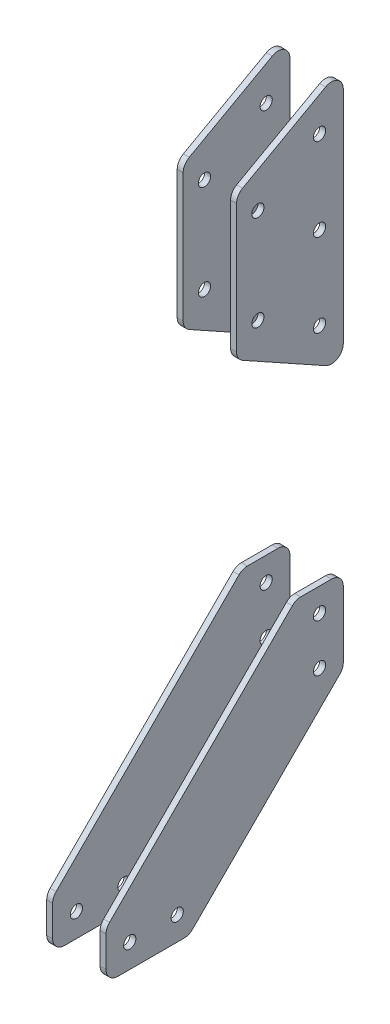
SolidWorks part; units mm, degrees
ref_plane "Front Plane" through (0, 0, 0) normal (0, 0, 1) x (1, 0, 0)
ref_plane "Top Plane" through (0, 0, 0) normal (0, 1, 0) x (1, 0, 0)
ref_plane "Right Plane" through (0, 0, 0) normal (1, 0, 0) x (0, 0, -1)
sketch "Sketch1" plane through (12.7, 0, 0) normal (1, 0, 0) x (0, 0, -1)
  line L0 (-44.45, 317.5) -> (-44.45, 241.3)
  line L1 (-44.45, 241.3) -> (12.7, 209.55)
  line L2 (12.7, 209.55) -> (12.7, 349.25)
  line L3 (12.7, 349.25) -> (-44.45, 317.5)
  line L4 (-44.45, 279.4) -> (12.7, 279.4) construction
  line L5 (0, 279.4) -> (-25.4, 279.4) construction
  line L6 (-44.45, 317.5) -> (-44.45, 241.3) construction
  line L7 (12.7, 406.4) -> (12.7, 12.7) construction
  line L8 (-12.7, 317.5) -> (-44.45, 317.5) construction
  line L9 (-12.7, 114.3) -> (-114.3, 12.7)
  line L10 (-114.3, 12.7) -> (-114.3, -12.7)
  line L11 (-114.3, -12.7) -> (-69.85, -12.7)
  line L12 (-69.85, -12.7) -> (12.7, 69.85)
  line L13 (12.7, 69.85) -> (12.7, 114.3)
  line L14 (12.7, 114.3) -> (-12.7, 114.3)
  line L15 (-355.6, -12.7) -> (152.4, -12.7) construction
  line L16 (-114.3, -12.7) -> (12.7, 114.3) construction
  dimension "D1" = 139.7
  dimension "D2" = 127
  dimension "D3" = 127
  dimension "D4" = 101.6
  dimension "D5" = 82.55
extrude "Boss-Extrude1" add sketch "Sketch1" along normal blind 3.175
sketch "Sketch4" plane through (15.875, 0, 0) normal (1, 0, 0) x (0, 0, -1)
  line L0 (0, 279.4) -> (0, 406.4) construction
  line L1 (0, 279.4) -> (0, 12.7) construction
  line L2 (-355.6, 0) -> (152.4, 0) construction
  line L3 (0, 323.85) -> (0, 234.95) construction
  line L5 (0, 101.6) -> (0, 76.2) construction
  line L7 (-101.6, 0) -> (-76.2, 0) construction
  line L9 (0, 101.6) -> (0, 114.3) construction
  line L10 (12.7, 114.3) -> (-12.7, 114.3) construction
  line L13 (-114.3, 0) -> (-101.6, 0) construction
  line L14 (-114.3, 12.7) -> (-114.3, -12.7) construction
  point P0 (0, 323.85)
  point P4 (0, 234.95)
  point P8 (0, 101.6)
  point P10 (0, 76.2)
  point P12 (-101.6, 0)
  point P16 (-76.2, 0)
  point P19 (0, 279.4)
  point P52 (-33.02, 304.8)
  point P55 (-33.02, 254)
  dimension "D1" = 88.9
  dimension "D2" = 25.4
  dimension "D3" = 12.7
hole_wizard "1/4 Clearance Hole1" positions "Sketch4" profile "Sketch3" hole size "1/4" standard "ANSI Inch" end condition through all
sketch "Sketch3" plane through (15.875, 323.85, 0) normal (0, 1, 0) x (0, 0, -1)
  line L0 (0, 0) -> (0, 3.175)
  line L1 (0, 3.175) -> (3.2639, 3.175)
  line L2 (3.2639, 3.175) -> (3.2639, 0)
  line L5 (3.2639, 0) -> (0, 0)
  line L11 (0, -6.35) -> (0, 107.95) construction
  dimension "Thru Hole Dia." = 6.5278
  dimension "Thru Hole Depth" = 3.175
fillet "Fillet1" radius 6.35 4 edges at (14.2875, 241.3, 44.45) (14.2875, 209.55, -12.7) (14.2875, 349.25, -12.7) (14.2875, 317.5, 44.45)
fillet "Fillet2" radius 6.35 6 edges at (14.2875, 12.7, 114.3) (14.2875, -12.7, 114.3) (14.2875, -12.7, 69.85) (14.2875, 69.85, -12.7) (14.2875, 114.3, -12.7) (14.2875, 114.3, 12.7)
mirror "Mirror1" about plane through (0, 0, 0) normal (1, 0, 0) of bodies 103 104
